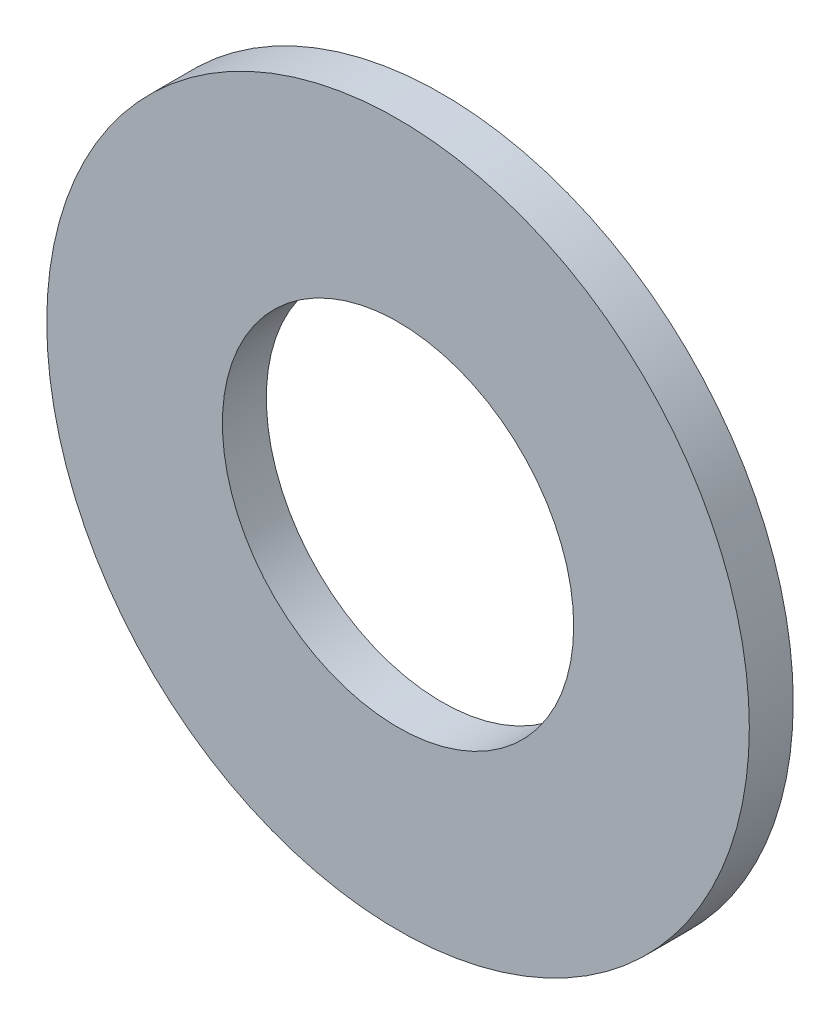
SolidWorks part; units mm, degrees
ref_plane "前视基准面" through (0, 0, 0) normal (0, 0, 1) x (1, 0, 0)
ref_plane "上视基准面" through (0, 0, 0) normal (0, 1, 0) x (1, 0, 0)
ref_plane "右视基准面" through (0, 0, 0) normal (1, 0, 0) x (0, 0, -1)
other "Configuration Table"
sketch "草图1" plane through (0, 0, 0) normal (0, 0, 1) x (1, 0, 0)
  circle A0 centre (-14.2008, -9.7272) radius 2
  circle A1 centre (-14.2008, -9.7272) radius 4
  dimension "D1" = 4
  dimension "D2" = 8
extrude "凸台-拉伸1" add sketch "草图1" along normal blind 0.5
